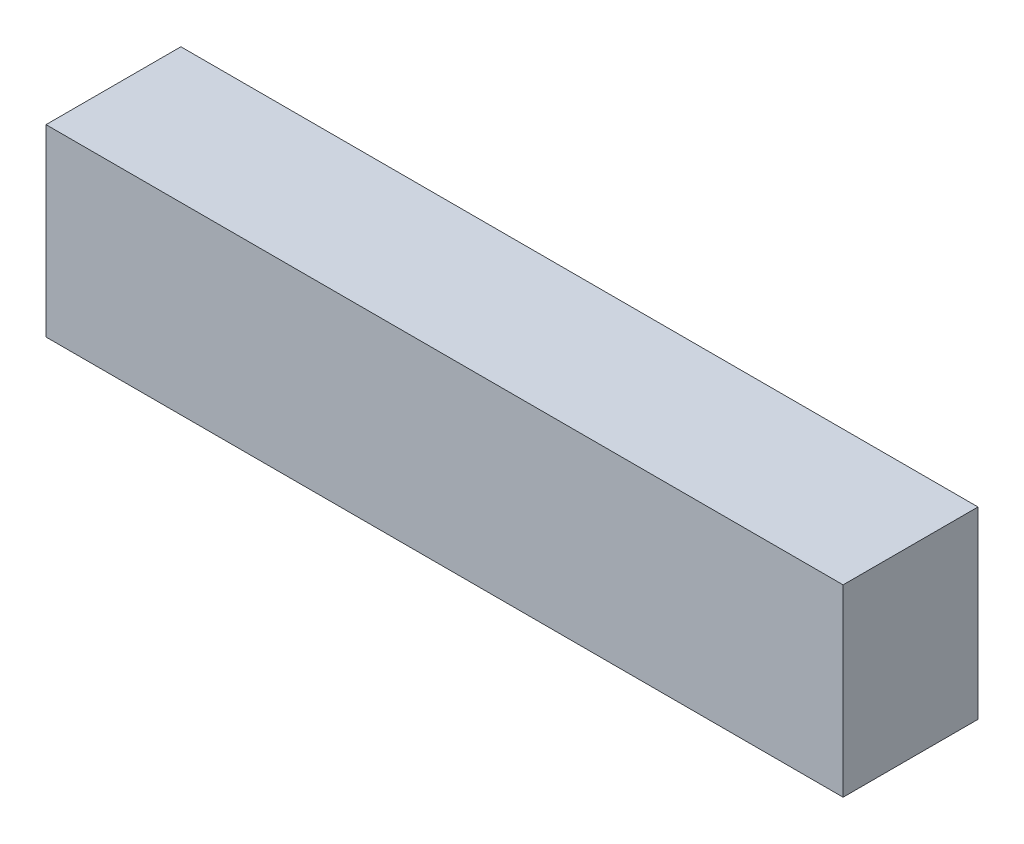
SolidWorks part; units mm, degrees
ref_plane "Front Plane" through (0, 0, 0) normal (0, 0, 1) x (1, 0, 0)
ref_plane "Top Plane" through (0, 0, 0) normal (0, 1, 0) x (1, 0, 0)
ref_plane "Right Plane" through (0, 0, 0) normal (1, 0, 0) x (0, 0, -1)
sketch "Sketch1" plane through (0, 0, 0) normal (0, 1, 0) x (1, 0, 0)
  line L1 (0, 0) -> (130, 0)
  line L2 (0, 0) -> (0, 22)
  line L3 (0, 22) -> (130, 22)
  line L4 (130, 0) -> (130, 22)
  dimension "D1" = 22
  dimension "D2" = 130
extrude "Boss-Extrude1" add sketch "Sketch1" along normal blind 30
